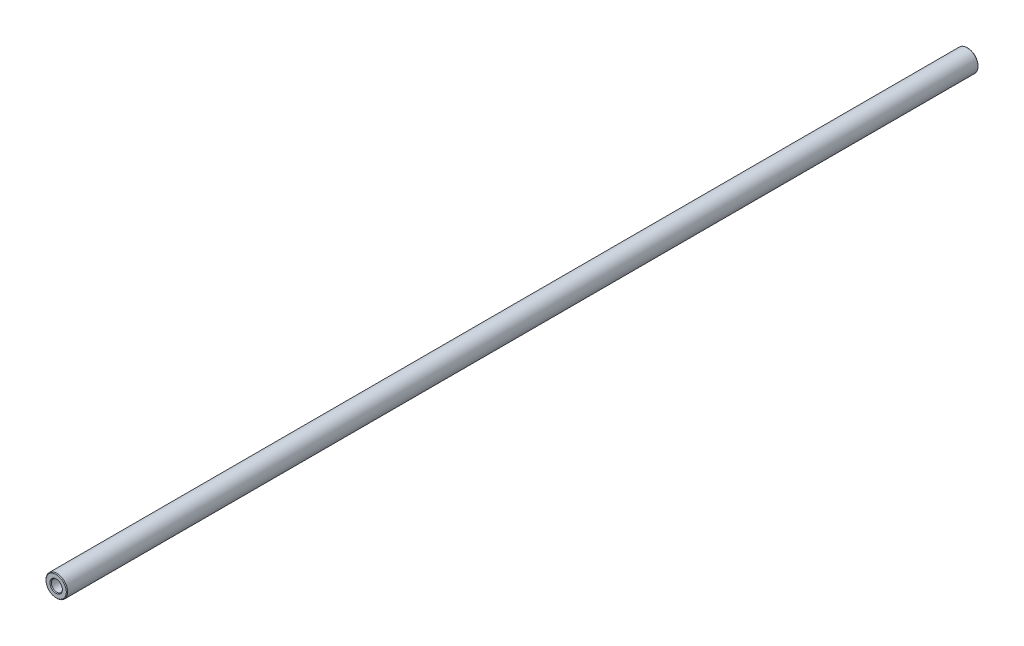
SolidWorks part; units mm, degrees
ref_plane "Front Plane" through (0, 0, 0) normal (0, 0, 1) x (1, 0, 0)
ref_plane "Top Plane" through (0, 0, 0) normal (0, 1, 0) x (1, 0, 0)
ref_plane "Right Plane" through (0, 0, 0) normal (1, 0, 0) x (0, 0, -1)
sketch "Sketch1" plane through (0, 0, 0) normal (0, 0, 1) x (1, 0, 0)
  circle A0 centre (0, 0) radius 3.9687
  dimension "D1" = 7.9375
extrude "Boss-Extrude1" add sketch "Sketch1" along normal blind 333.375
sketch "Sketch2" plane through (0, 0, 333.375) normal (0, 0, 1) x (1, 0, 0)
  circle A0 centre (0, 0) radius 2.032
  dimension "D1" = 4.064
extrude "Cut-Extrude1" cut sketch "Sketch2" against normal blind 12.7
sketch "Sketch3" plane through (0, 0, 0) normal (0, 0, -1) x (-1, 0, 0)
  circle A0 centre (0, 0) radius 2.032
  dimension "D1" = 4.064
extrude "Cut-Extrude2" cut sketch "Sketch3" against normal blind 12.7
chamfer "Chamfer1" distance 0.254 angle 45 4 edges at (3.9687, 0, 333.375) (2.032, 0, 333.375) (3.9687, 0, 0) (-2.032, 0, 0)
